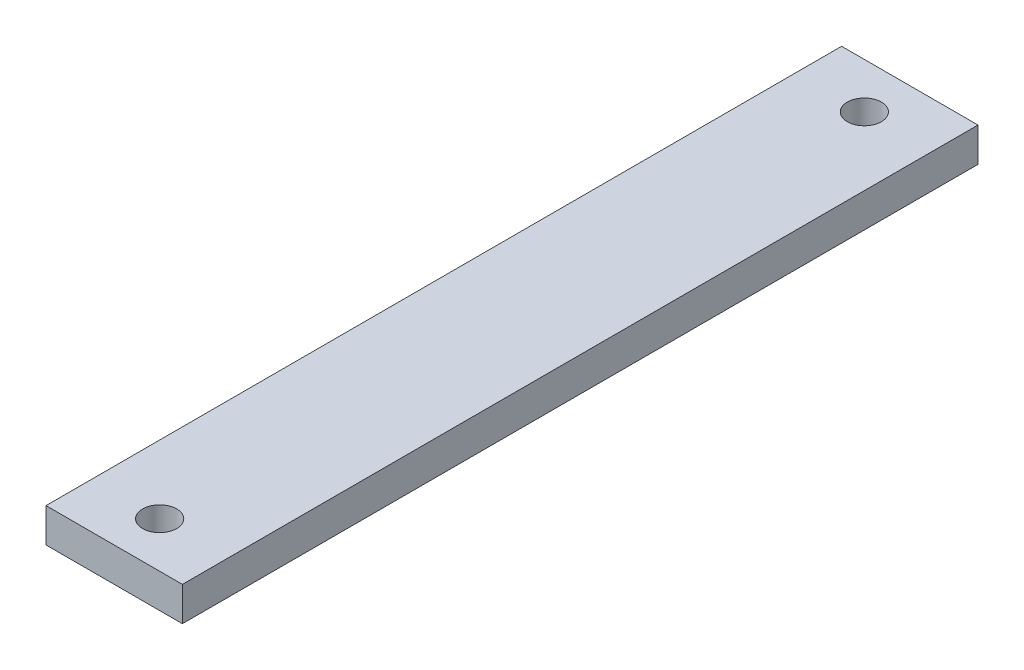
SolidWorks part; units mm, degrees
ref_plane "前视基准面" through (0, 0, 0) normal (0, 0, 1) x (1, 0, 0)
ref_plane "上视基准面" through (0, 0, 0) normal (0, 1, 0) x (1, 0, 0)
ref_plane "右视基准面" through (0, 0, 0) normal (1, 0, 0) x (0, 0, -1)
sketch "草图1" plane through (0, 0, 0) normal (0, 1, 0) x (1, 0, 0)
  line L1 (0, 0) -> (12, 0)
  line L2 (0, 0) -> (0, 70)
  line L3 (0, 70) -> (12, 70)
  line L4 (12, 0) -> (12, 70)
  dimension "D1" = 70
  dimension "D2" = 12
extrude "凸台-拉伸1" add sketch "草图1" along normal blind 3
sketch "草图2" plane through (0, 3, 0) normal (0, 1, 0) x (1, 0, 0)
  line L0 (6, 4) -> (6, 0) construction
  line L1 (0, 0) -> (12, 0) construction
  line L2 (6, 66) -> (6, 70) construction
  line L3 (12, 70) -> (0, 70) construction
  circle A0 centre (6, 4) radius 1.5
  circle A1 centre (6, 66) radius 1.5
  dimension "D2" = 3
  dimension "D1" = 62
extrude "切除-拉伸1" cut sketch "草图2" against normal through all
